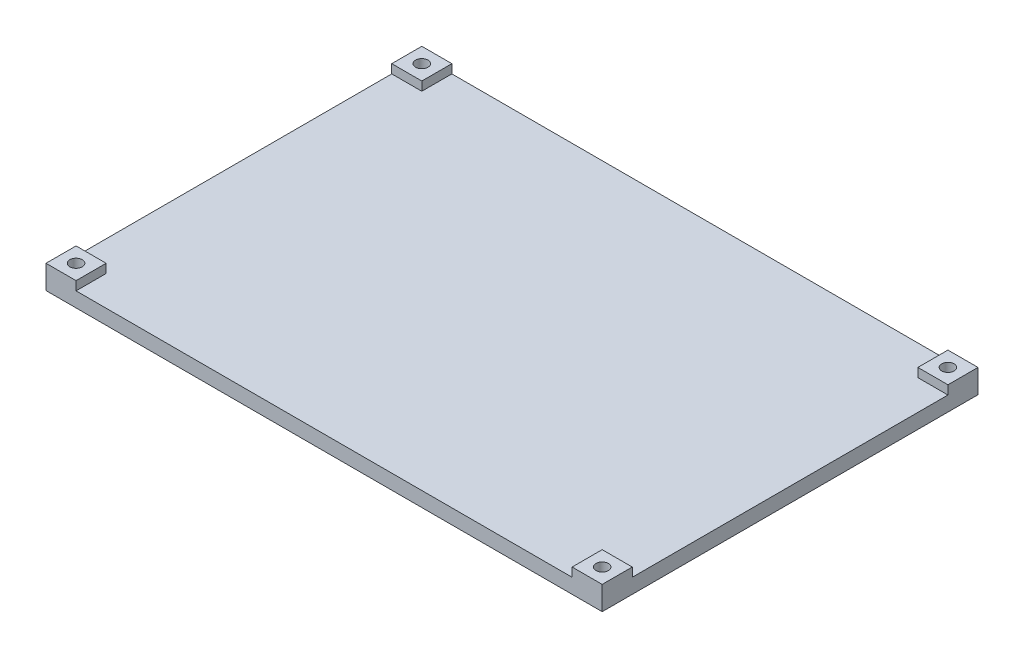
SolidWorks part; units mm, degrees
ref_plane "前视基准面" through (0, 0, 0) normal (0, 0, 1) x (1, 0, 0)
ref_plane "上视基准面" through (0, 0, 0) normal (0, 1, 0) x (1, 0, 0)
ref_plane "右视基准面" through (0, 0, 0) normal (1, 0, 0) x (0, 0, -1)
other "Configuration Table"
sketch "草图1" plane through (0, 0, 0) normal (0, 1, 0) x (1, 0, 0)
  line L0 (-44.45, 29.21) -> (44.45, -29.21) construction
  line L1 (-46.99, -31.75) -> (46.99, -31.75)
  line L2 (-46.99, -31.75) -> (-46.99, 31.75)
  line L3 (-46.99, 31.75) -> (46.99, 31.75)
  line L4 (46.99, -31.75) -> (46.99, 31.75)
  line L5 (-46.99, -31.75) -> (46.99, 31.75) construction
  line L6 (-46.99, 31.75) -> (46.99, -31.75) construction
  circle A1 centre (-44.45, 29.21) radius 1.05
  circle A3 centre (-44.45, -29.21) radius 1.05
  circle A5 centre (44.45, 29.21) radius 1.05
  circle A7 centre (44.45, -29.21) radius 1.05
  point P0 (0, 0)
  dimension "D3" = 2.1
  dimension "D4" = 2.54
  dimension "D1" = 93.98
  dimension "D2" = 88.9
  dimension "D5" = 63.5
extrude "凸台-拉伸1" add sketch "草图1" along normal blind 4 contours L3 L4 L1 L2 | A1 | A5 | A7 | A3
sketch "草图2" plane through (0, 4, 0) normal (0, 1, 0) x (1, 0, 0)
  line L0 (-46.99, -31.75) -> (-46.99, 31.75) construction
  line L1 (-46.99, 31.75) -> (-41.91, 31.75)
  line L2 (-46.99, 31.75) -> (-46.99, 26.67)
  line L3 (-46.99, 26.67) -> (-41.91, 26.67)
  line L4 (-41.91, 31.75) -> (-41.91, 26.67)
  line L5 (-46.99, -31.75) -> (46.99, -31.75) construction
  line L6 (-46.99, -26.67) -> (-41.91, -26.67)
  line L7 (-46.99, -26.67) -> (-46.99, -31.75)
  line L8 (-46.99, -31.75) -> (-41.91, -31.75)
  line L9 (-41.91, -26.67) -> (-41.91, -31.75)
  line L10 (46.99, -31.75) -> (41.91, -31.75)
  line L11 (46.99, -31.75) -> (46.99, -26.67)
  line L12 (46.99, -26.67) -> (41.91, -26.67)
  line L13 (41.91, -31.75) -> (41.91, -26.67)
  line L14 (-46.99, 31.75) -> (46.99, 31.75) construction
  line L15 (46.99, 31.75) -> (41.91, 31.75)
  line L16 (46.99, 31.75) -> (46.99, 26.67)
  line L17 (46.99, 26.67) -> (41.91, 26.67)
  line L18 (41.91, 31.75) -> (41.91, 26.67)
  line L19 (46.99, -31.75) -> (46.99, 31.75) construction
  line L21 (-46.99, 31.75) -> (-41.91, 26.67) construction
  circle A0 centre (-44.45, 29.21) radius 1.05 construction
  point P24 (-44.45, 29.21)
extrude "切除-拉伸1" cut sketch "草图2" against normal blind 1.5 flip side to cut
sketch "草图3" plane through (0, 0, 0) normal (0, -1, 0) x (1, 0, 0)
  line L2 (-36.99, 21.75) -> (0, 21.75) construction
  line L3 (0, 21.75) -> (36.99, 21.75) construction
  line L4 (36.99, 21.75) -> (46.99, 21.75) construction
  line L5 (46.99, 31.75) -> (46.99, -31.75) construction
  line L6 (0, 31.75) -> (0, 21.75) construction
  line L7 (-46.99, 31.75) -> (46.99, 31.75) construction
  line L8 (0, 21.75) -> (0, 3.9167) construction
  line L9 (0, 3.9167) -> (0, -21.75) construction
  line L10 (0, -21.75) -> (0, -31.75) construction
  line L11 (-46.99, -31.75) -> (46.99, -31.75) construction
  circle A0 centre (-36.99, 21.75) radius 2.6
  circle A1 centre (-36.99, -21.75) radius 2.6
  circle A2 centre (0, 21.75) radius 2.6
  circle A3 centre (0, -21.75) radius 2.6
  circle A4 centre (36.99, 21.75) radius 2.6
  circle A5 centre (36.99, -21.75) radius 2.6
  dimension "D1" = 5.2
  dimension "D2" = 10
  dimension "D3" = 10
extrude "切除-拉伸2" cut sketch "草图3" against normal blind 0.8
